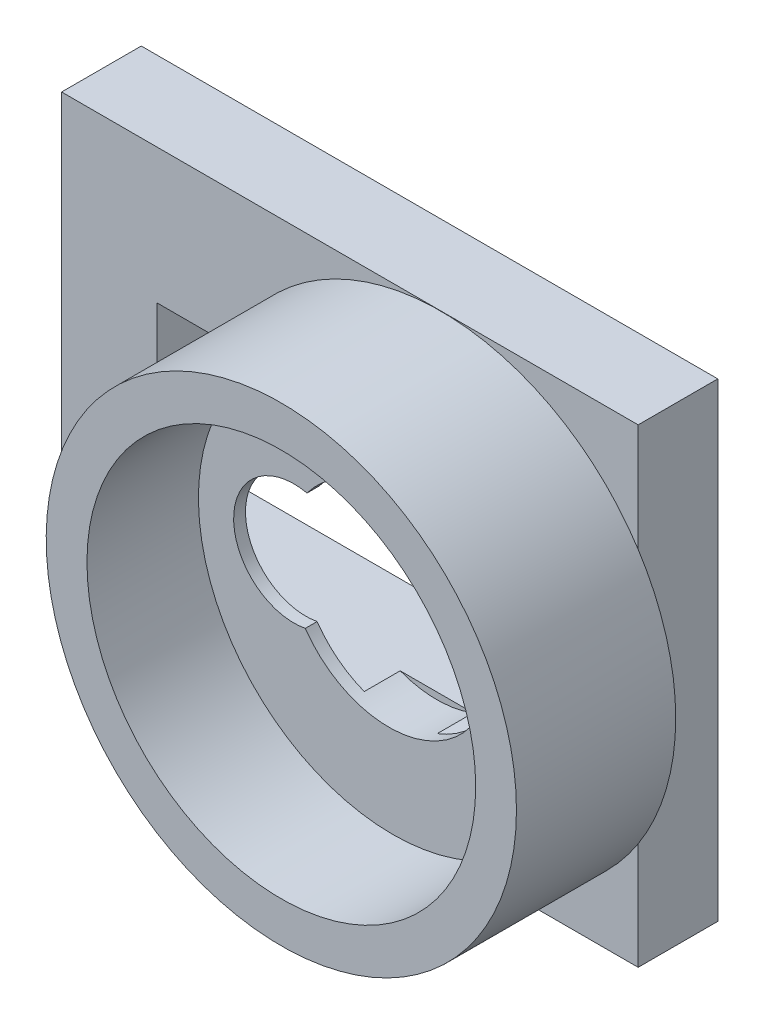
SolidWorks part; units mm, degrees
material "ABS"
ref_plane "Plan de face" through (0, 0, 0) normal (0, 0, 1) x (1, 0, 0)
ref_plane "Plan de dessus" through (0, 0, 0) normal (0, 1, 0) x (1, 0, 0)
ref_plane "Plan de droite" through (0, 0, 0) normal (1, 0, 0) x (0, 0, -1)
sketch "Esquisse1" plane through (0, 0, 0) normal (0, 0, 1) x (1, 0, 0)
  line L1 (-13, -0.5) -> (23.2, -0.5)
  line L2 (-13, -0.5) -> (-13, -30)
  line L3 (-13, -30) -> (23.2, -30)
  line L4 (23.2, -0.5) -> (23.2, -30)
sketch "Esquisse2" plane through (0, 0, 0) normal (0, 0, 1) x (1, 0, 0)
  line L1 (21.05, -8.973) -> (-12.003, -8.973)
  line L2 (21.05, -8.973) -> (21.05, -21.345)
  line L3 (21.05, -21.345) -> (-12.003, -21.345)
  line L4 (-12.003, -8.973) -> (-12.003, -21.345)
sketch "Esquisse3" plane through (0, 0, 0) normal (0, 0, 1) x (1, 0, 0)
  line L0 (21.05, -21.345) -> (-12.003, -21.345) construction
  line L1 (21.05, -8.973) -> (16.4916, -8.973)
  line L2 (21.05, -8.973) -> (21.05, -21.345)
  line L3 (21.05, -21.345) -> (16.4916, -21.345)
  line L4 (16.4916, -8.973) -> (16.4916, -21.345)
  line L6 (-12.003, -8.973) -> (-7.003, -8.973)
  line L7 (-12.003, -8.973) -> (-12.003, -21.353)
  line L8 (-12.003, -21.353) -> (-7.003, -21.353)
  line L9 (-7.003, -8.973) -> (-7.003, -21.353)
sketch "Esquisse4" plane through (0, 0, 0) normal (0, 0, 1) x (1, 0, 0)
  arc A0 (5.2992, -19.0172) -> (5.4087, -11.6055) centre (10.5484, -15.3881) ccw
  arc A1 (5.4087, -11.6055) -> (5.2992, -19.0172) centre (4.5853, -15.3) ccw
  circle A2 centre (10.5484, -15.3881) radius 12.3981
sketch "Esquisse5" plane through (0, 0, 0) normal (0, 0, 1) x (1, 0, 0)
  circle A0 centre (10.7946, -15.2758) radius 12.2036
  circle A1 centre (10.7946, -15.2758) radius 14.7637
extrude "Boss.-Extru.1" add sketch "Esquisse1" along normal blind 5
extrude "Enlèv. mat.-Extru.1" cut sketch "Esquisse2" along normal blind 5
extrude "Boss.-Extru.2" add sketch "Esquisse3" against normal blind 3.5 from offset 5
extrude "Boss.-Extru.7" add sketch "Esquisse5" along normal blind 10 from offset 5
extrude "Boss.-Extru.5" add sketch "Esquisse4" along normal blind 2 and the other way blind 1 from offset 6
sketch "Esquisse6" plane through (-13, 0, 0) normal (-1, 0, 0) x (0, 0, 1)
  line L1 (5, -8.973) -> (7.2565, -8.973)
  line L2 (5, -8.973) -> (5, -21.345)
  line L3 (5, -21.345) -> (7.2565, -21.345)
  line L4 (7.2565, -8.973) -> (7.2565, -21.345)
extrude "Enlèv. mat.-Extru.3" cut sketch "Esquisse6" against normal up to surface (29.4916 mm away) up to face at (16.4916, -15.2354, 3.8333)
